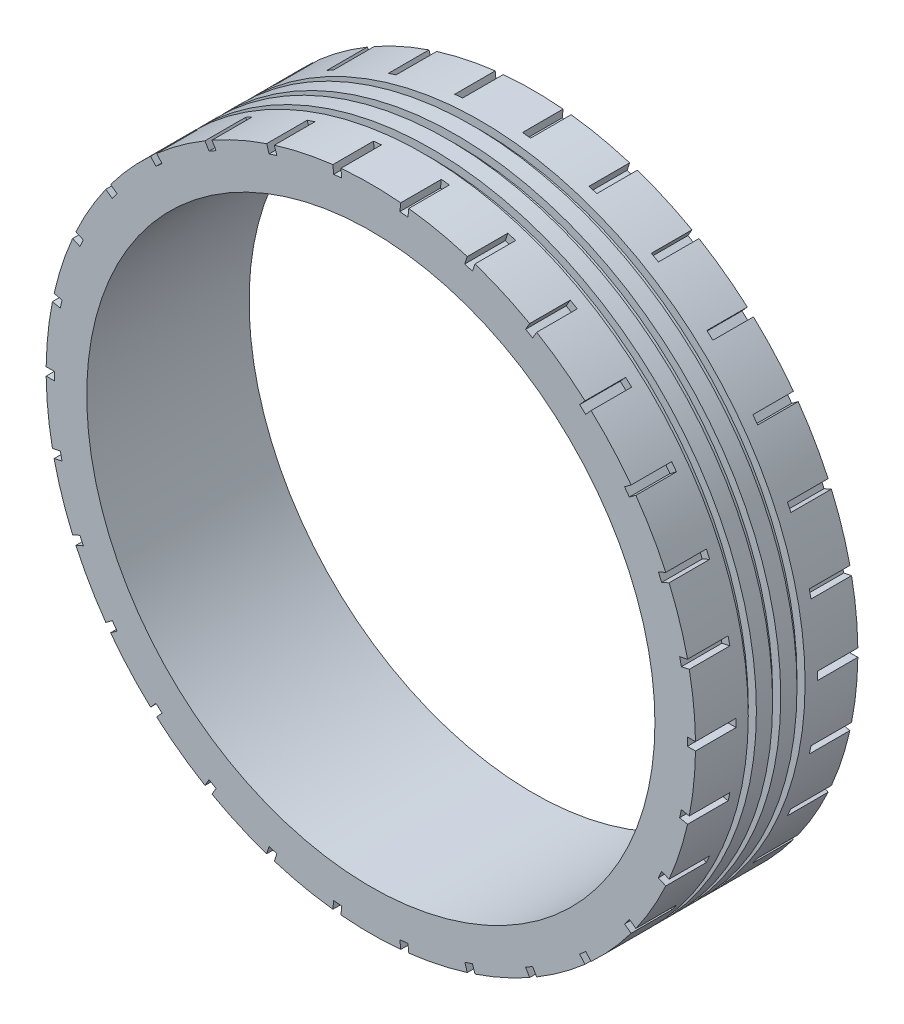
SolidWorks part; units mm, degrees
ref_plane "前视基准面" through (0, 0, 0) normal (0, 0, 1) x (1, 0, 0)
ref_plane "上视基准面" through (0, 0, 0) normal (0, 1, 0) x (1, 0, 0)
ref_plane "右视基准面" through (0, 0, 0) normal (1, 0, 0) x (0, 0, -1)
sketch "草图1" plane through (0, 0, 0) normal (0, 0, 1) x (1, 0, 0)
  circle A0 centre (0, 0) radius 35
  circle A1 centre (0, 0) radius 40
  dimension "D1" = 70
  dimension "D2" = 80
extrude "凸台-拉伸1" add sketch "草图1" along normal blind 20
sketch "草图2" plane through (0, 0, 0) normal (0, 0, -1) x (-1, 0, 0)
  line L1 (39, -0.5) -> (41, -0.5)
  line L2 (39, -0.5) -> (39, 0.5)
  line L3 (39, 0.5) -> (41, 0.5)
  line L4 (41, -0.5) -> (41, 0.5)
  line L5 (39, -0.5) -> (41, 0.5) construction
  line L6 (39, 0.5) -> (41, -0.5) construction
  circle A0 centre (0, 0) radius 40 construction
  point P0 (40, 0)
  dimension "D1" = 1
  dimension "D2" = 2
extrude "切除-拉伸1" cut sketch "草图2" against normal blind 5
pattern_circular "阵列(圆周)1" count 30 over 360 about axis through (0, 0, 0) along (0, 0, 1) of "切除-拉伸1"
ref_plane "基准面4" through (0, 0, 10) normal (0, 0, 1) x (1, 0, 0)
mirror "镜向1" about plane through (0, 0, 10) normal (0, 0, 1) of "阵列(圆周)1", "切除-拉伸1"
sketch "草图4" plane through (0, 0, 10) normal (0, 0, 1) x (1, 0, 0)
  circle A0 centre (0, 0) radius 39.0032
  circle A1 centre (0, 0) radius 45
extrude "切除-拉伸2" cut sketch "草图4" against normal mid plane 1
pattern_linear "阵列(线性)1" count 2 spacing 3 along (0, 0, 1) count 2 spacing 3 along (0, 0, -1) of "切除-拉伸2"
